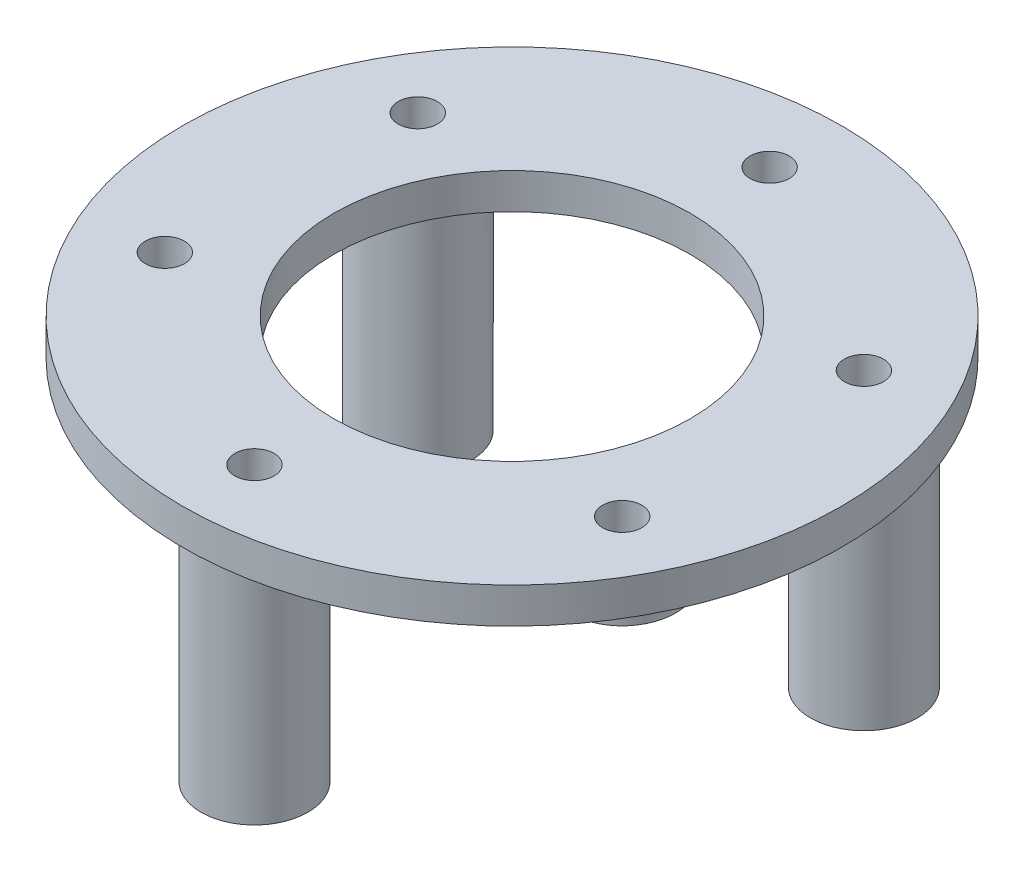
SolidWorks part; units mm, degrees
ref_plane "Спереди" through (0, 0, 0) normal (0, 0, 1) x (1, 0, 0)
ref_plane "Сверху" through (0, 0, 0) normal (0, 1, 0) x (1, 0, 0)
ref_plane "Справа" through (0, 0, 0) normal (1, 0, 0) x (0, 0, -1)
sketch "Эскиз1" plane through (0, 0, 0) normal (0, 1, 0) x (1, 0, 0)
  line L0 (0, 0) -> (0, 14.46) construction
  line L1 (0, 0) -> (-12.8378, -6.6545) construction
  line L2 (0, 0) -> (12.8378, -6.6545) construction
  circle A0 centre (0, 0) radius 10
  circle A1 centre (0, 0) radius 18.5
  circle A2 centre (0, 14.46) radius 1.1
  circle A3 centre (12.8378, -6.6545) radius 1.1
  circle A4 centre (-12.8378, -6.6545) radius 1.1
  dimension "D1" = 20
  dimension "D2" = 37
  dimension "D3" = 2.2
  dimension "D4" = 117.4
  dimension "D5" = 117.4
  dimension "D6" = 14.46
extrude "Бобышка-Вытянуть1" add sketch "Эскиз1" along normal blind 2
sketch "Эскиз2" plane through (0, 2, 0) normal (0, 1, 0) x (1, 0, 0)
  circle A0 centre (0, 14.46) radius 1.1
  circle A1 centre (0, 14.46) radius 3
  circle A2 centre (-12.8378, -6.6545) radius 1.1
  circle A3 centre (-12.8378, -6.6545) radius 3
  circle A4 centre (12.8378, -6.6545) radius 1.1
  circle A5 centre (12.8378, -6.6545) radius 3
  dimension "D1" = 6
  dimension "D2" = 2.2
extrude "Бобышка-Вытянуть2" add sketch "Эскиз2" against normal blind 1.2 from surface at -2 starting at face at (0, 0, 18.5)
sketch "Эскиз3" plane through (0, 2, 0) normal (0, 1, 0) x (1, 0, 0)
  line L0 (0, 0) -> (0, 19.3962) construction
  line L1 (0, 0) -> (-12.5227, 7.23) construction
  line L2 (0, 0) -> (0, -14.46) construction
  line L3 (0, 0) -> (12.5227, 7.23) construction
  circle A0 centre (-12.5227, 7.23) radius 1.1
  circle A1 centre (12.5227, 7.23) radius 1.1
  circle A2 centre (0, -14.46) radius 1.1
  dimension "D2" = 2.2
  dimension "D1" = 14.46
  dimension "D3" = 120
  dimension "D4" = 120
extrude "Вырез-Вытянуть1" cut sketch "Эскиз3" against normal through all
sketch "Эскиз4" plane through (0, 0, 0) normal (0, -1, 0) x (1, 0, 0)
  circle A0 centre (-12.5227, -7.23) radius 1.1
  circle A1 centre (-12.5227, -7.23) radius 3
  circle A2 centre (0, 14.46) radius 1.1
  circle A3 centre (0, 14.46) radius 3
  circle A4 centre (12.5227, -7.23) radius 1.1
  circle A5 centre (12.5227, -7.23) radius 3
  dimension "D1" = 2.2
  dimension "D2" = 6
extrude "Бобышка-Вытянуть3" add sketch "Эскиз4" along normal blind 13.4
sketch "Эскиз5" plane through (0, 0, 0) normal (0, -1, 0) x (1, 0, 0)
  line L0 (0, 0) -> (-9.6213, -16.6646) construction
  line L1 (0, 0) -> (0, -24.9549) construction
  line L3 (-8.384, -16.5215) -> (-6.384, -13.0574)
  line L4 (-8.384, -16.5215) -> (-10.116, -15.5215)
  line L5 (-10.116, -15.5215) -> (-8.116, -12.0574)
  line L6 (-6.384, -13.0574) -> (-8.116, -12.0574)
  line L7 (-8.384, -16.5215) -> (-8.116, -12.0574) construction
  line L8 (-10.116, -15.5215) -> (-6.384, -13.0574) construction
  point P3 (-8.25, -14.2894)
  point P9 (-7.5719, -14.359)
  dimension "D1" = 30
  dimension "D2" = 2
  dimension "D3" = 4
  dimension "D4" = 16.5
extrude "Вырез-Вытянуть2" cut sketch "Эскиз5" against normal blind 0.44
